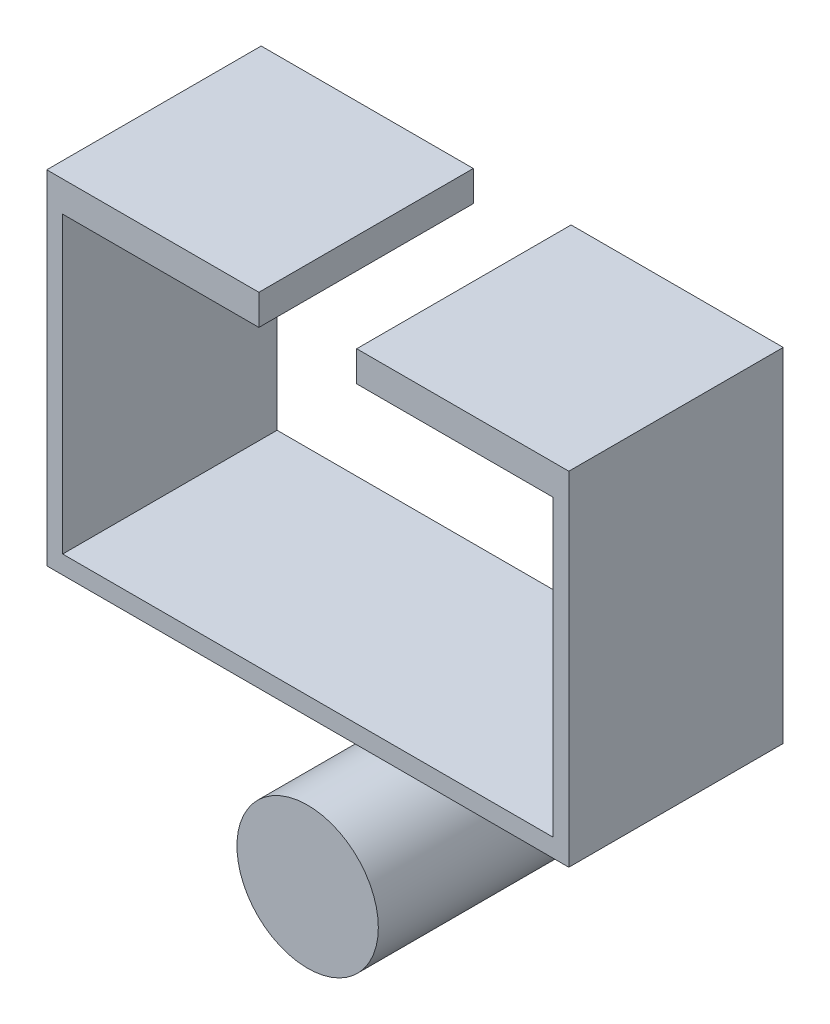
SolidWorks part; units mm, degrees
ref_plane "Front Plane" through (0, 0, 0) normal (0, 0, 1) x (1, 0, 0)
ref_plane "Top Plane" through (0, 0, 0) normal (0, 1, 0) x (1, 0, 0)
ref_plane "Right Plane" through (0, 0, 0) normal (1, 0, 0) x (0, 0, -1)
sketch "Sketch1" plane through (0, 0, 0) normal (0, 0, 1) x (1, 0, 0)
  line L12 (-33.7617, 0) -> (33.7617, 0)
  line L13 (-33.7617, 0) -> (-33.7617, 44.3635)
  line L14 (-33.7617, 44.3635) -> (-6.3246, 44.3635)
  line L15 (-6.3246, 44.3635) -> (-6.3246, 40.4265)
  line L16 (-6.3246, 40.4265) -> (-31.7043, 40.4265)
  line L17 (-31.7043, 40.4265) -> (-31.7043, 2.3519)
  line L18 (-31.7043, 2.3519) -> (31.7043, 2.3519)
  line L19 (31.7043, 2.3519) -> (31.7043, 40.4265)
  line L20 (31.7043, 40.4265) -> (6.3246, 40.4265)
  line L21 (6.3246, 40.4265) -> (6.3246, 44.3635)
  line L22 (6.3246, 44.3635) -> (33.7617, 44.3635)
  line L23 (33.7617, 44.3635) -> (33.7617, 0)
  point P3 (0, 0)
  dimension "D4" = 3.937
  dimension "D5" = 2.0574
  dimension "D6" = 2.0574
  dimension "D2" = 2.3519
  dimension "D3" = 25.3797
  dimension "D1" = 63.4086
  dimension "D7" = 38.0746
extrude "Boss-Extrude1" add sketch "Sketch1" along normal blind 27.7315
sketch "Sketch2" plane through (0, 0, 0) normal (0, 0, 1) x (1, 0, 0)
  line L5 (-9.144, 0) -> (9.144, 0)
  line L6 (-9.144, 0) -> (-9.144, -19.05)
  line L7 (9.144, 0) -> (9.144, -19.05)
  arc A1 (-9.144, -19.05) -> (9.144, -19.05) centre (0, -19.05) ccw
  point P2 (0, 0)
  dimension "D3" = 9.144
  dimension "D1" = 18.288
  dimension "D2" = 19.05
extrude "Boss-Extrude2" add sketch "Sketch2" along normal blind 2.3519
sketch "Sketch4" plane through (0, 0, 2.3519) normal (0, 0, 1) x (1, 0, 0)
  circle A2 centre (0, -19.05) radius 9.144
  arc A3 (-9.144, -19.05) -> (9.144, -19.05) centre (0, -19.05) ccw construction
extrude "Boss-Extrude3" add sketch "Sketch4" along normal blind 25.4
equation "\"a\"= 0.498"
equation "\"b\"= 0.9992"
equation "\"c\"= 1.499"
equation "\"Overall Width\"= \"a\" + \"b\" + \"b\""
equation "\"Pin Diameter\"= 0.72"
equation "\"Hanger Width\"= 0.72"
equation "\"Wall Width\"= 0.081"
equation "\"Pin Length\"= 1"
equation "\"Flange Width\"= 0.155"
equation "\"Flange Length\"= 600 / ( 2 * 0.36 * 9000 )"
equation "\"Bracket Width\"= \"b\" + \"Flange Length\""
equation "\"D1@Boss-Extrude1\"=\"Bracket Width\""
equation "\"D1@Boss-Extrude2\"=\"Flange Length\""
equation "\"D1@Boss-Extrude3\"=\"Pin Length\""
equation "\"D1@Sketch2\"=\"Hanger Width\""
equation "\"Pin to Base\"= 0.75"
equation "\"D2@Sketch2\"=\"Pin to Base\""
equation "\"D4@Sketch1\"=\"Flange Width\""
equation "\"D2@Sketch1\"=\"Flange Length\""
equation "\"Flange Height\"= 0.0876"
equation "\"D1@Sketch1\"=\"Overall Width\""
equation "\"D7@Sketch1\"=\"c\""
equation "\"D3@Sketch1\"=\"b\""
equation "\"D6@Sketch1\"=\"Wall Width\""
equation "\"D5@Sketch1\"=\"Wall Width\""
